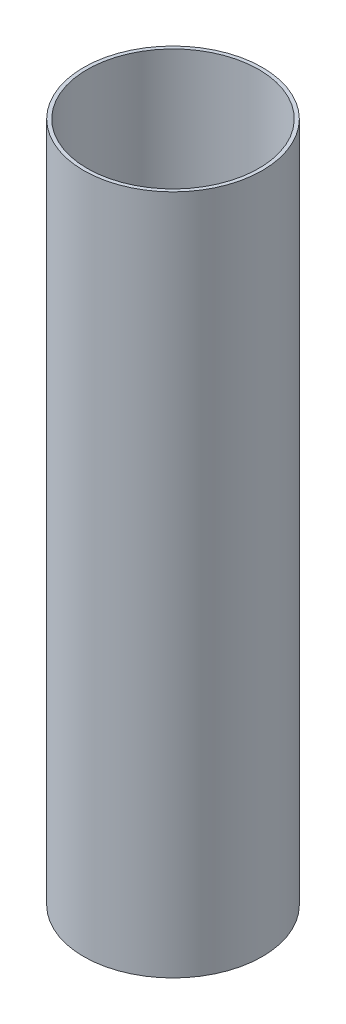
SolidWorks part; units mm, degrees
material "1060 Сплав"
ref_plane "Спереди" through (0, 0, 0) normal (0, 0, 1) x (1, 0, 0)
ref_plane "Сверху" through (0, 0, 0) normal (0, 1, 0) x (1, 0, 0)
ref_plane "Справа" through (0, 0, 0) normal (1, 0, 0) x (0, 0, -1)
sketch "Эскиз1" plane through (0, 0, 0) normal (0, 1, 0) x (1, 0, 0)
  circle A0 centre (0, 0) radius 50
  circle A1 centre (0, 0) radius 48
  dimension "D1" = 100
  dimension "D2" = 96
extrude "Бобышка-Вытянуть1" add sketch "Эскиз1" along normal blind 381
